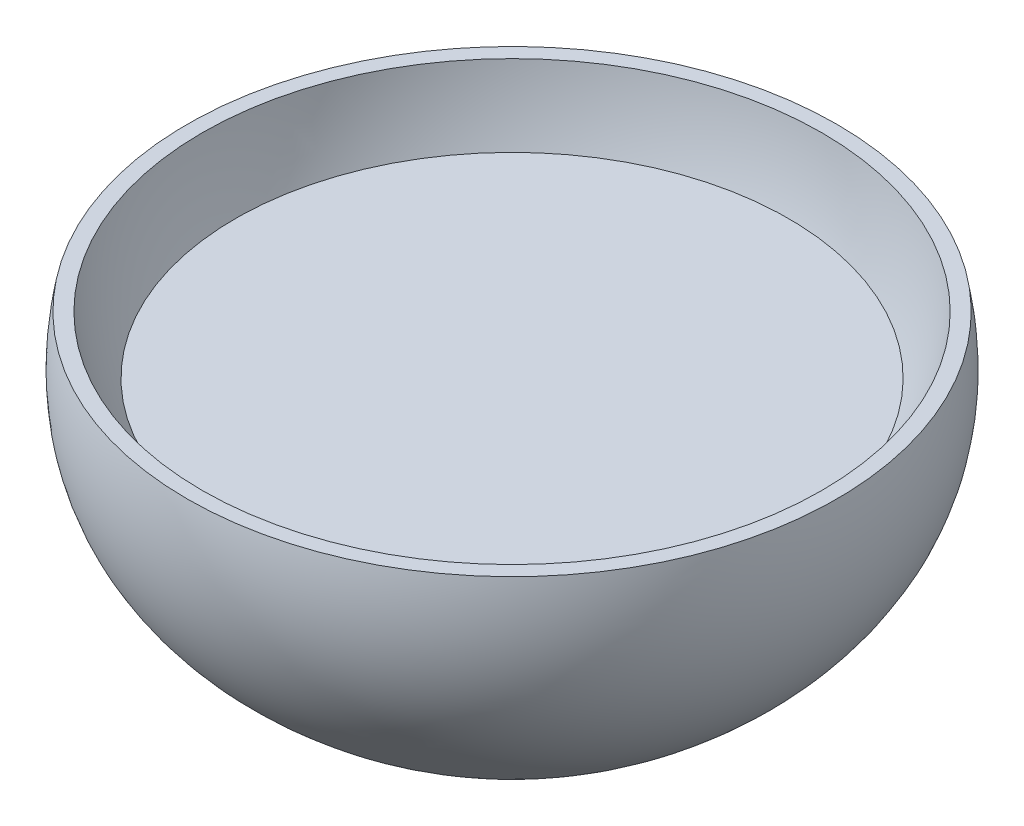
SolidWorks part; units mm, degrees
ref_plane "Front Plane" through (0, 0, 0) normal (0, 0, 1) x (1, 0, 0)
ref_plane "Top Plane" through (0, 0, 0) normal (0, 1, 0) x (1, 0, 0)
ref_plane "Right Plane" through (0, 0, 0) normal (1, 0, 0) x (0, 0, -1)
sketch "Sketch2" plane through (0, 0, 0) normal (0, 0, 1) x (1, 0, 0)
  line L0 (0, 0) -> (0, 4.9675)
  line L2 (53.4672, 62.1126) -> (50.7856, 62.1126)
  line L4 (0, 4.9675) -> (-5.173, 4.9675)
  line L5 (0, 4.9675) -> (0, 0)
  line L6 (0, 0) -> (-5.173, 0)
  line L7 (-5.173, 4.9675) -> (-5.173, 0)
  arc A1 (0, 4.9675) -> (50.7856, 62.1126) centre (-19.3652, 73.317) ccw
  spline S0 degree 2 poles (0, 0) (61.2557, 20.5594) (53.4672, 62.1126) knots 0 0 0 1 1 1
revolve "Revolve6" add sketch "Sketch2" angle 360 about L7
sketch "Sketch3" plane through (0, 62.1126, 0) normal (0, 1, 0) x (1, 0, 0)
  circle A1 centre (-5.173, 0) radius 55.9586
extrude "Boss-Extrude6" add sketch "Sketch3" against normal blind 40.894 draft 30 separate body
sketch "Sketch4" plane through (0, 62.1126, 0) normal (0, 1, 0) x (1, 0, 0)
  circle A0 centre (-5.173, 0) radius 55.9586
extrude "Cut-Extrude1" cut sketch "Sketch4" against normal blind 10.414 draft 30
